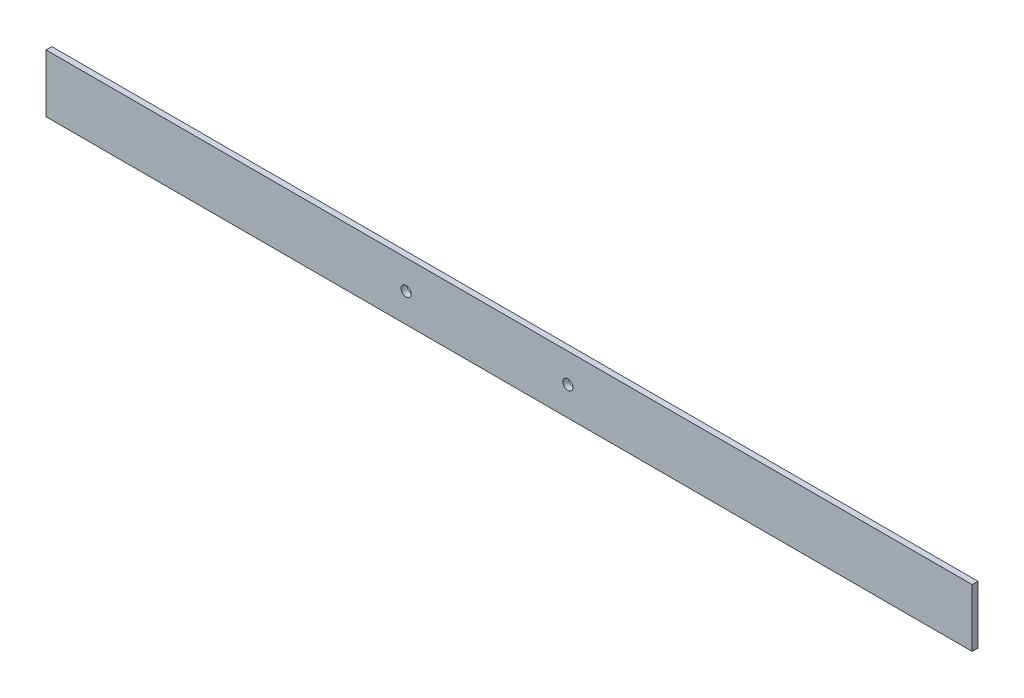
SolidWorks part; units mm, degrees
ref_plane "Płaszczyzna przednia" through (0, 0, 0) normal (0, 0, 1) x (1, 0, 0)
ref_plane "Płaszczyzna górna" through (0, 0, 0) normal (0, 1, 0) x (1, 0, 0)
ref_plane "Płaszczyzna prawa" through (0, 0, 0) normal (1, 0, 0) x (0, 0, -1)
sketch "Szkic1" plane through (0, 0, 0) normal (0, 0, 1) x (1, 0, 0)
  line L0 (400, 0) -> (400, 50)
  line L1 (0, 0) -> (800, 0)
  line L2 (0, 0) -> (0, 50)
  line L3 (0, 50) -> (800, 50)
  line L4 (800, 0) -> (800, 50)
  circle A0 centre (311.1, 25) radius 4.365
  circle A1 centre (450.8, 25) radius 4.365
  dimension "D5" = 8.73
  dimension "D6" = 8.73
  dimension "D1" = 800
  dimension "D2" = 50
extrude "Dodanie-wyciągnięcie1" add sketch "Szkic1" along normal blind 5 contours L3 L2 L1 L0 A0 | L1 L4 L3 L0 A1
